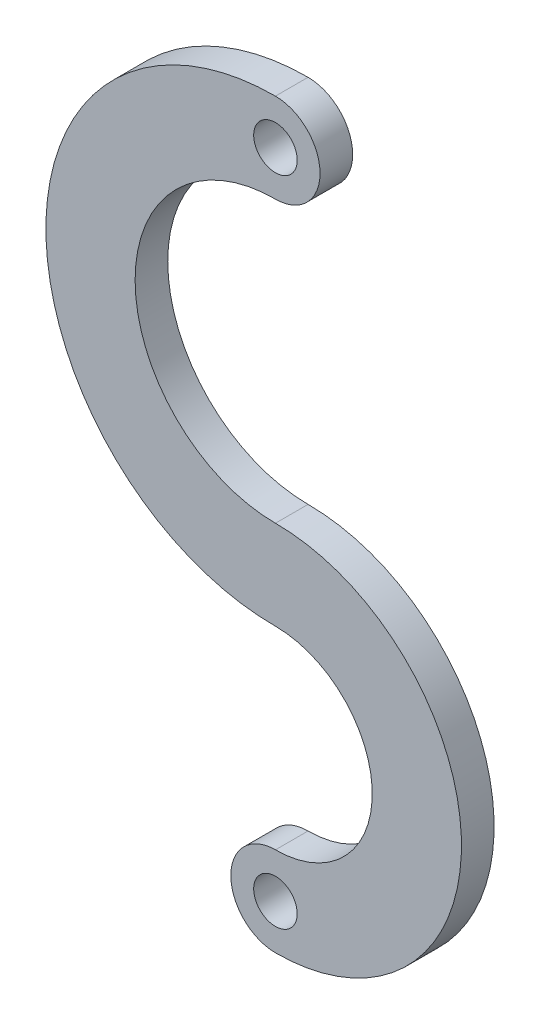
SolidWorks part; units mm, degrees
ref_plane "Front Plane" through (0, 0, 0) normal (0, 0, 1) x (1, 0, 0)
ref_plane "Top Plane" through (0, 0, 0) normal (0, 1, 0) x (1, 0, 0)
ref_plane "Right Plane" through (0, 0, 0) normal (1, 0, 0) x (0, 0, -1)
sketch "Sketch1" plane through (0, 0, 0) normal (0, 0, 1) x (1, 0, 0)
  arc A0 (0, 1.4087) -> (0, -15.5913) centre (0, -7.0913) ccw construction
  arc A1 (0, 3.4587) -> (0, -17.6413) centre (0, -7.0913) ccw
  arc A2 (0, -0.6413) -> (0, -13.5413) centre (0, -7.0913) ccw
  arc A3 (0, -0.6413) -> (0, 3.4587) centre (0, 1.4087) ccw
  arc A5 (0, -15.5913) -> (0, -28.5913) centre (0, -22.0913) cw construction
  arc A6 (0, -30.6413) -> (0, -13.5413) centre (0, -22.0913) ccw
  arc A7 (0, -26.5413) -> (0, -17.6413) centre (0, -22.0913) ccw
  arc A8 (0, -26.5413) -> (0, -30.6413) centre (0, -28.5913) ccw
  circle A9 centre (0, 1.4087) radius 1
  circle A10 centre (0, -28.5913) radius 1
  point P3 (-8.5, -7.0913)
  point P10 (6.5, -22.0913)
  point P18 (0, 1.4087)
  dimension "D1" = 17
  dimension "D2" = 2.05
  dimension "D3" = 2.05
  dimension "D5" = 6.45
  dimension "D6" = 10.55
  dimension "D9" = 4.45
  dimension "D12" = 2
  dimension "D4" = 30
  dimension "D7" = 8.5
  dimension "D8" = 6.5
  dimension "D10" = 6.5
  dimension "D11" = 23.5
extrude "Boss-Extrude1" add sketch "Sketch1" along normal blind 1.5
